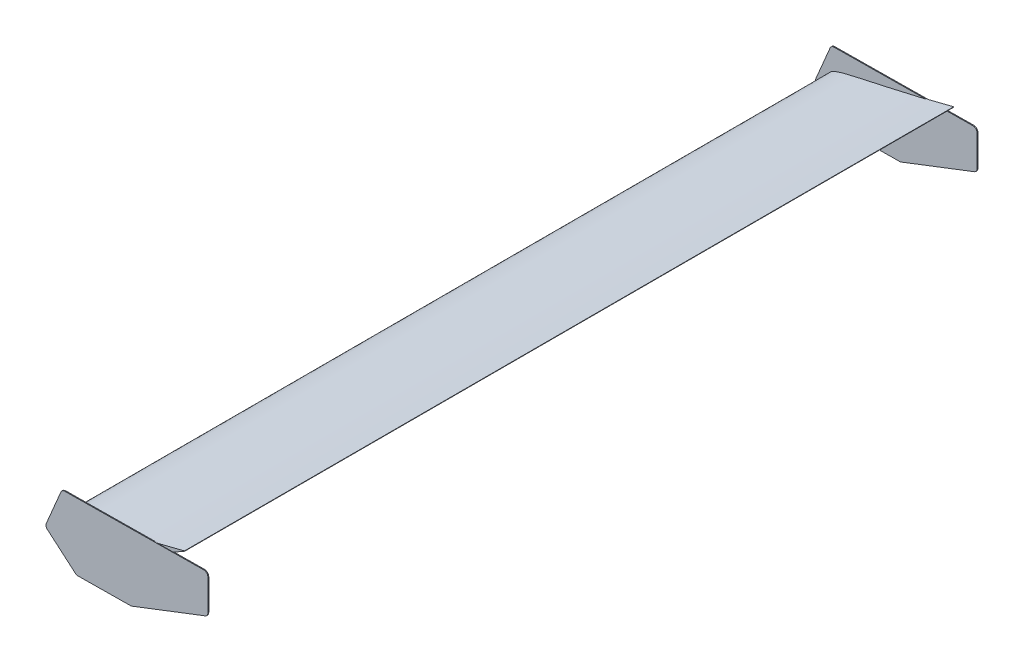
SolidWorks part; units mm, degrees
ref_plane "Front Plane" through (0, 0, 0) normal (0, 0, 1) x (1, 0, 0)
ref_plane "Top Plane" through (0, 0, 0) normal (0, 1, 0) x (1, 0, 0)
ref_plane "Right Plane" through (0, 0, 0) normal (1, 0, 0) x (0, 0, -1)
curve "Airfoil Curve"
  spline degree 3 poles (300, -0.39, 0) (295.0052, -1.7497, 0) (285.0396, -4.4626, 0) (265.0756, -9.3952, 0) (240.11, -14.8452, 0) (210.0811, -20.2176, 0) (180.0755, -24.6212, 0) (150.0532, -27.7624, 0) (120.0335, -29.7214, 0) (94.9726, -29.7413, 0) (74.963, -28.3569, 0) (59.9355, -26.5335, 0) (44.8755, -23.8445, 0) (32.3958, -20.6106, 0) (22.3952, -17.3445, 0) (14.8545, -14.2611, 0) (8.4203, -10.9265, 0) (2.8355, -6.9378, 0) (-2.0261, -0.5226, 0) (3.2214, 4.3836, 0) (8.5759, 6.3095, 0) (14.9528, 7.6093, 0) (22.4839, 8.2702, 0) (32.4958, 8.738, 0) (45.0031, 8.7029, 0) (60.0065, 8.2831, 0) (74.9993, 7.4837, 0) (94.9994, 6.5483, 0) (119.9952, 5.3479, 0) (150.0009, 4.2208, 0) (179.9969, 2.9692, 0) (209.9958, 1.9031, 0) (239.9971, 1.119, 0) (264.9992, 0.7209, 0) (284.9995, 0.4587, 0) (294.9999, 0.4129, 0) (300, 0.39, 0) knots 0 0 0 0 0.025305 0.050488 0.10052 0.150191 0.199587 0.24874 0.297716 0.346601 0.371103 0.395726 0.42057 0.445825 0.458702 0.47192 0.485786 0.493461 0.506863 0.516148 0.522766 0.535269 0.547551 0.559786 0.584229 0.608681 0.633151 0.657622 0.706558 0.755482 0.804406 0.85332 0.902221 0.951113 0.975557 1 1 1 1
ref_plane "Plane1" through (300, -0.39, 0) normal (-0.9649, -0.2627, 0) x (0, 0, 1)
sketch "AirfoilSketch" plane through (0, 0, 0) normal (0, 0, 1) x (1, 0, 0)
  line L2 (0, 0) -> (350.3559, 0) construction
  line B0 (289.778, 77.6458) -> (289.9789, 76.8921)
  line B1 (0, 0) -> (289.778, 77.6458) construction
  spline B2 degree 3 poles (289.9789, 76.8921) (285.5028, 74.2918) (276.5721, 69.1037) (258.5522, 59.1955) (235.8326, 47.4992) (208.2006, 34.5737) (180.3415, 22.5903) (152.1412, 11.8225) (123.6389, 2.1975) (99.4287, -4.2764) (79.7376, -8.0925) (64.7474, -10.2011) (49.5029, -11.4817) (36.6114, -11.5712) (26.1069, -10.9911) (18.0265, -9.954) (10.9505, -8.3891) (4.5268, -5.9734) (-1.8232, -1.0268) (1.9836, 5.0654) (6.6615, 8.3054) (12.4885, 11.2039) (19.5953, 13.7822) (29.1489, 16.8129) (41.2432, 20.0004) (55.8486, 23.4591) (70.5414, 26.5482) (90.1077, 30.7957) (114.5693, 36.0738) (143.8529, 42.7131) (173.1593, 49.2296) (202.4206, 55.9261) (231.6117, 62.8956) (255.8729, 68.9506) (275.2659, 73.8486) (284.9407, 76.3801) (289.778, 77.6458) knots 0 0 0 0 0.025305 0.050488 0.10052 0.150191 0.199587 0.24874 0.297716 0.346601 0.371103 0.395726 0.42057 0.445825 0.458702 0.47192 0.485786 0.493461 0.506863 0.516148 0.522766 0.535269 0.547551 0.559786 0.584229 0.608681 0.633151 0.657622 0.706558 0.755482 0.804406 0.85332 0.902221 0.951113 0.975557 1 1 1 1
  dimension "AoA_Rear_Wing" = 15
sketch_block_instance "AirfoilBlock-1"
sketch_block "AirfoilBlock"
extrude "Rear Wing" add sketch "AirfoilSketch" along normal mid plane 1800
sketch "Endplate Sketch" plane through (0, 0, 900) normal (0, 0, 1) x (1, 0, 0)
  line L0 (4.1984, 59.4067) -> (-35.2909, -33.8505)
  line L1 (-35.2909, -33.8505) -> (38.2575, -96.7338)
  line L2 (4.1984, 59.4067) -> (345.6673, 62.9082)
  line L3 (345.6673, 62.9082) -> (345.6673, -26.3186)
  line L5 (38.2575, -96.7338) -> (166.2751, -95.4211)
  line L6 (166.2751, -95.4211) -> (345.6673, -26.3186)
  point P2 (152.1224, -101.9226)
  point P6 (313.3454, 63.1358)
  point P7 (345.6673, -26.3186)
  point P8 (345.6673, 62.9082)
  point P9 (4.1984, 59.4067)
  point P10 (-35.2909, -33.8505)
extrude "Endplate" add sketch "Endplate Sketch" along normal mid plane 2
fillet "Endplate Fillet" radius 10 6 edges at (345.6673, 62.9082, 900) (345.6673, -26.3186, 900) (166.2751, -95.4211, 900) (4.1984, 59.4067, 900) (-35.2909, -33.8505, 900) (38.2575, -96.7338, 900)
mirror "Mirror3" about plane through (0, 0, 0) normal (0, 0, 1) of "Endplate Fillet", "Endplate"
